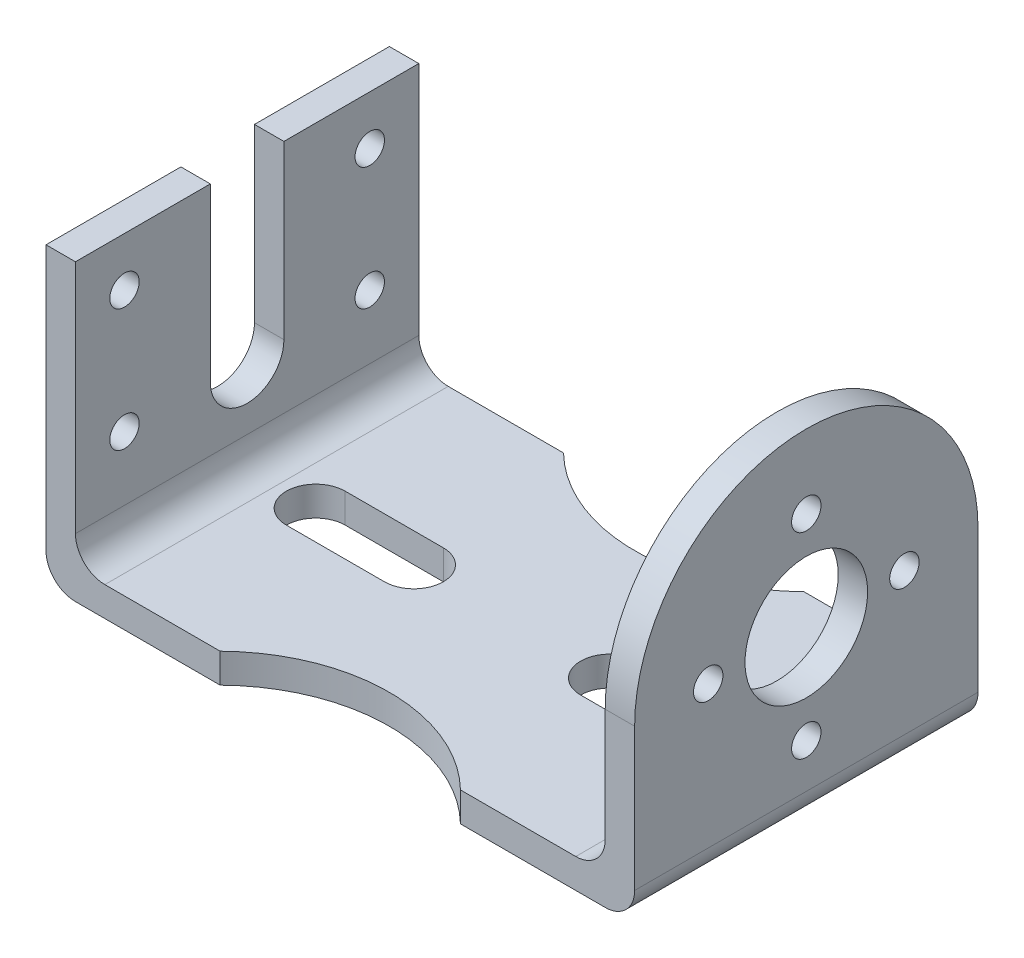
SolidWorks part; units mm, degrees
ref_plane "Front Plane" through (0, 0, 0) normal (0, 0, 1) x (1, 0, 0)
ref_plane "Top Plane" through (0, 0, 0) normal (0, 1, 0) x (1, 0, 0)
ref_plane "Right Plane" through (0, 0, 0) normal (1, 0, 0) x (0, 0, -1)
sketch "Sketch1" plane through (0, 0, 0) normal (0, 0, 1) x (1, 0, 0)
  line L0 (-54, 0) -> (54, 0)
  line L1 (60, 6) -> (60, 60)
  line L2 (-60, 6) -> (-60, 60)
  line L3 (-60, 60) -> (-54, 60)
  line L4 (-54, 60) -> (-54, 12)
  line L5 (-48, 6) -> (48, 6)
  line L6 (54, 12) -> (54, 60)
  line L7 (54, 60) -> (60, 60)
  arc A0 (48, 6) -> (54, 12) centre (48, 12) ccw
  arc A1 (-54, 12) -> (-48, 6) centre (-48, 12) ccw
  arc A2 (-54, 0) -> (-60, 6) centre (-54, 6) cw
  arc A3 (54, 0) -> (60, 6) centre (54, 6) ccw
  point P4 (0, 0)
  point P17 (-60, 0)
  point P20 (60, 0)
  dimension "D7" = 6
  dimension "D8" = 6
  dimension "D1" = 120
  dimension "D2" = 60
  dimension "D3" = 60
  dimension "D4" = 6
  dimension "D5" = 6
  dimension "D6" = 6
extrude "Boss-Extrude1" add sketch "Sketch1" against normal blind 70
sketch "Sketch2" plane through (60, 0, 0) normal (1, 0, 0) x (0, 0, -1)
  line L0 (70, 0) -> (0, 0) construction
  line L1 (0, 6) -> (0, 60) construction
  line L2 (70, 6) -> (70, 60) construction
  line L3 (0, 35) -> (0, 60)
  line L4 (0, 60) -> (10.5051, 60)
  line L5 (70, 60) -> (0, 60) construction
  line L6 (70, 35) -> (70, 60)
  line L7 (70, 60) -> (59.4949, 60)
  arc A0 (70, 35) -> (59.4949, 60) centre (35, 35) ccw
  arc A1 (10.5051, 60) -> (0, 35) centre (35, 35) ccw
  point P0 (35, 35)
  dimension "D1" = 35
  dimension "D2" = 35
extrude "Cut-Extrude1" cut sketch "Sketch2" against normal blind 33
sketch "Sketch3" plane through (60, 0, 0) normal (1, 0, 0) x (0, 0, -1)
  line L2 (10.5051, 60) -> (59.4949, 60)
  arc A0 (59.4949, 60) -> (10.5051, 60) centre (35, 35) ccw
  point P0 (35, 35)
extrude "Boss-Extrude2" add sketch "Sketch3" against normal blind 6
sketch "Sketch4" plane through (60, 0, 0) normal (1, 0, 0) x (0, 0, -1)
  circle A0 centre (35, 35) radius 12.5
  point P0 (35, 35)
extrude "Cut-Extrude2" cut sketch "Sketch4" against normal blind 16
sketch "Sketch5" plane through (60, 0, 0) normal (1, 0, 0) x (0, 0, -1)
  circle A1 centre (35, 55) radius 3
  circle A2 centre (55, 35) radius 3
  circle A3 centre (35, 15) radius 3
  circle A4 centre (15, 35) radius 3
  point P14 (35, 35)
  dimension "D1" = 4
extrude "Cut-Extrude3" cut sketch "Sketch5" against normal blind 16
sketch "Sketch6" plane through (-60, 0, 0) normal (-1, 0, 0) x (0, 0, 1)
  line L0 (-70, 0) -> (0, 0) construction
  line L1 (-42.5, 60) -> (-27.5, 60)
  line L2 (-70, 60) -> (0, 60) construction
  line L4 (-27.5, 60) -> (-27.5, 25)
  line L6 (-42.5, 25) -> (-42.5, 60)
  line L7 (-70, 60) -> (-70, 6) construction
  line L8 (0, 60) -> (0, 6) construction
  arc A0 (-42.5, 25) -> (-27.5, 25) centre (-35, 25) ccw
  circle A1 centre (-60, 50) radius 3
  circle A2 centre (-60, 25) radius 3
  circle A3 centre (-10, 50) radius 3
  circle A4 centre (-10, 25) radius 3
  point P0 (-35, 35)
  point P9 (-35, 60)
  point P26 (-60, 32.6397)
  point P27 (0, 0)
  point P28 (0, 0)
  dimension "D7" = 10
  dimension "D1" = 35
  dimension "D2" = 35
  dimension "D3" = 27.5
  dimension "D4" = 27.5
  dimension "D5" = 15
  dimension "D6" = 35
  dimension "D8" = 10
  dimension "D9" = 10
  dimension "D10" = 10
  dimension "D11" = 25
  dimension "D12" = 25
extrude "Cut-Extrude4" cut sketch "Sketch6" against normal blind 16
sketch "Sketch7" plane through (0, 6, 0) normal (0, 1, 0) x (1, 0, 0)
  line L0 (0, 0) -> (0, 70) construction
  line L1 (48, 70) -> (-48, 70) construction
  line L2 (-40, 41) -> (-20, 41)
  line L3 (-20, 29) -> (-40, 29)
  line L4 (20, 29) -> (40, 29)
  line L5 (40, 41) -> (20, 41)
  line L6 (-24.4949, 0) -> (24.4949, 0)
  line L7 (48, 0) -> (-48, 0) construction
  line L8 (-20, 35) -> (20, 35) construction
  line L9 (-24.4949, 70) -> (24.4949, 70)
  arc A0 (-20, 29) -> (-20, 41) centre (-20, 35) ccw
  arc A1 (-40, 41) -> (-40, 29) centre (-40, 35) ccw
  arc A2 (40, 41) -> (40, 29) centre (40, 35) cw
  arc A3 (20, 29) -> (20, 41) centre (20, 35) cw
  arc A4 (24.4949, 0) -> (-24.4949, 0) centre (0, -25) ccw
  arc A5 (24.4949, 70) -> (-24.4949, 70) centre (0, 95) cw
  point P6 (-20, 35)
  point P7 (-40, 35)
  point P20 (40, 35)
  point P21 (20, 35)
  point P22 (0, 10)
  point P30 (0, 60)
  dimension "D3" = 10
  dimension "D1" = 20
  dimension "D2" = 20
extrude "Cut-Extrude5" cut sketch "Sketch7" against normal blind 16
